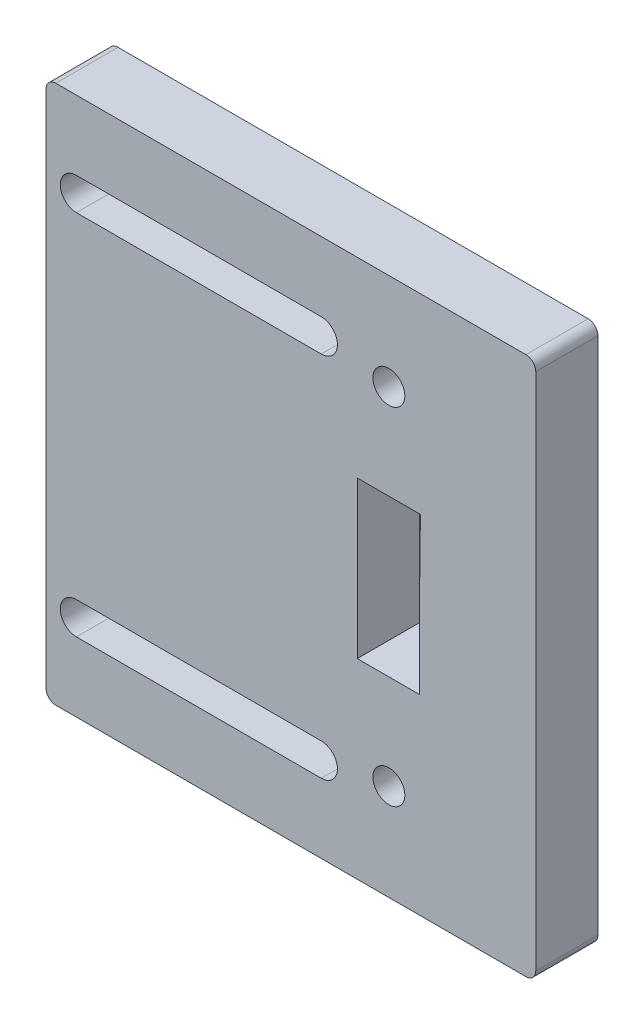
SolidWorks part; units mm, degrees
ref_plane "Front Plane" through (0, 0, 0) normal (0, 0, 1) x (1, 0, 0)
ref_plane "Top Plane" through (0, 0, 0) normal (0, 1, 0) x (1, 0, 0)
ref_plane "Right Plane" through (0, 0, 0) normal (1, 0, 0) x (0, 0, -1)
sketch "Sketch1" plane through (0, 0, 0) normal (0, 0, 1) x (1, 0, 0)
  line L0 (70, -110) -> (70, -90.31) construction
  line L1 (0, 0) -> (100, 0)
  line L2 (0, 0) -> (0, -110)
  line L3 (0, -110) -> (100, -110)
  line L4 (100, 0) -> (100, -110)
  line L6 (70, -39.0256) -> (76.45, -39.0256)
  line L8 (76.25, -70.9756) -> (70, -70.9756)
  line L9 (70, -70.9756) -> (63.55, -70.9756)
  line L10 (63.55, -70.9756) -> (63.55, -39.0256)
  line L11 (63.55, -39.0256) -> (70, -39.0256)
  line L12 (70, 0) -> (70, -19.69) construction
  line L14 (76.45, -39.0256) -> (76.25, -55)
  line L15 (76.25, -55) -> (76.25, -70.9756)
  dimension "D6" = 30
  dimension "D1" = 110
  dimension "D2" = 31.95
  dimension "D3" = 12.9
  dimension "D4" = 19.69
  dimension "D5" = 19.69
  dimension "D7" = 15.9744
  dimension "D8" = 70
extrude "Boss-Extrude2" add sketch "Sketch1" along normal blind 12.7
sketch "Sketch8" plane through (0, 0, 0) normal (0, 0, -1) x (-1, 0, 0)
  line L1 (-70, -110) -> (-70, -90.31) construction
  dimension "D1" = 19.69
  dimension "D2" = 30
hole_wizard "CSK for 1/4 Flat Head Machine Screw3" positions "Sketch9" profile "Sketch10" countersink size "1/4" standard "ANSI Inch" end condition through all
sketch "Sketch9" plane through (0, 0, 0) normal (0, 0, -1) x (-1, 0, 0)
  point P0 (-70, -90.31)
sketch "Sketch10" plane through (70, -90.31, 0) normal (1, 0, 0) x (0, 1, 0)
  line L0 (0, 0) -> (0, 12.7)
  line L1 (0, 12.7) -> (3.2639, 12.7)
  line L2 (3.2639, 12.7) -> (3.2639, 3.6524)
  line L3 (3.2639, 3.6524) -> (6.4389, 0)
  line L5 (6.4389, 0) -> (0, 0)
  line L6 (-3.2639, 3.6524) -> (-6.4389, 0) construction
  line L11 (0, -6.35) -> (0, 107.95) construction
  dimension "Thru Hole Dia." = 6.5278
  dimension "Thru Hole Depth" = 12.7
  dimension "Near C'Sink Dia." = 12.8778
  dimension "Near C'Sink Angle" = 82
sketch "Sketch11" plane through (0, 0, 0) normal (0, 0, -1) x (-1, 0, 0)
  line L0 (-70, 0) -> (-70, -19.69)
  dimension "D1" = 19.69
  dimension "D2" = 30
hole_wizard "CSK for 1/4 Flat Head Machine Screw4" positions "Sketch12" profile "Sketch13" countersink size "1/4" standard "ANSI Inch" end condition through all
sketch "Sketch12" plane through (0, 0, 0) normal (0, 0, -1) x (-1, 0, 0)
  point P0 (-70, -19.69)
sketch "Sketch13" plane through (70, -19.69, 0) normal (1, 0, 0) x (0, 1, 0)
  line L0 (0, 0) -> (0, 12.7)
  line L1 (0, 12.7) -> (3.2639, 12.7)
  line L2 (3.2639, 12.7) -> (3.2639, 3.6524)
  line L3 (3.2639, 3.6524) -> (6.4389, 0)
  line L5 (6.4389, 0) -> (0, 0)
  line L6 (-3.2639, 3.6524) -> (-6.4389, 0) construction
  line L11 (0, -6.35) -> (0, 107.95) construction
  dimension "Thru Hole Dia." = 6.5278
  dimension "Thru Hole Depth" = 12.7
  dimension "Near C'Sink Dia." = 12.8778
  dimension "Near C'Sink Angle" = 82
fillet "Fillet1" radius 2 4 edges at (0, 0, 6.35) (100, 0, 6.35) (0, -110, 6.35) (100, -110, 6.35)
sketch "Sketch15" plane through (0, 0, 0) normal (0, 0, -1) x (-1, 0, 0)
  line L0 (-56.2003, -14.19) -> (-6.2003, -14.19)
  line L1 (-56.2003, -20.79) -> (-6.2003, -20.79)
  line L2 (0, -55) -> (-82.6046, -55) construction
  line L3 (0, -2) -> (0, -108) construction
  line L4 (-56.2003, -89.21) -> (-6.2003, -89.21)
  line L5 (-56.2003, -95.81) -> (-6.2003, -95.81)
  arc A0 (-6.2003, -14.19) -> (-6.2003, -20.79) centre (-6.2003, -17.49) cw
  arc A1 (-56.2003, -20.79) -> (-56.2003, -14.19) centre (-56.2003, -17.49) cw
  arc A2 (-6.2003, -95.81) -> (-6.2003, -89.21) centre (-6.2003, -92.51) ccw
  arc A3 (-56.2003, -89.21) -> (-56.2003, -95.81) centre (-56.2003, -92.51) ccw
  dimension "D3" = 3.3
  dimension "D4" = 68.42
  dimension "D1" = 50
  dimension "D2" = 50
extrude "Cut-Extrude1" cut sketch "Sketch15" against normal through all
